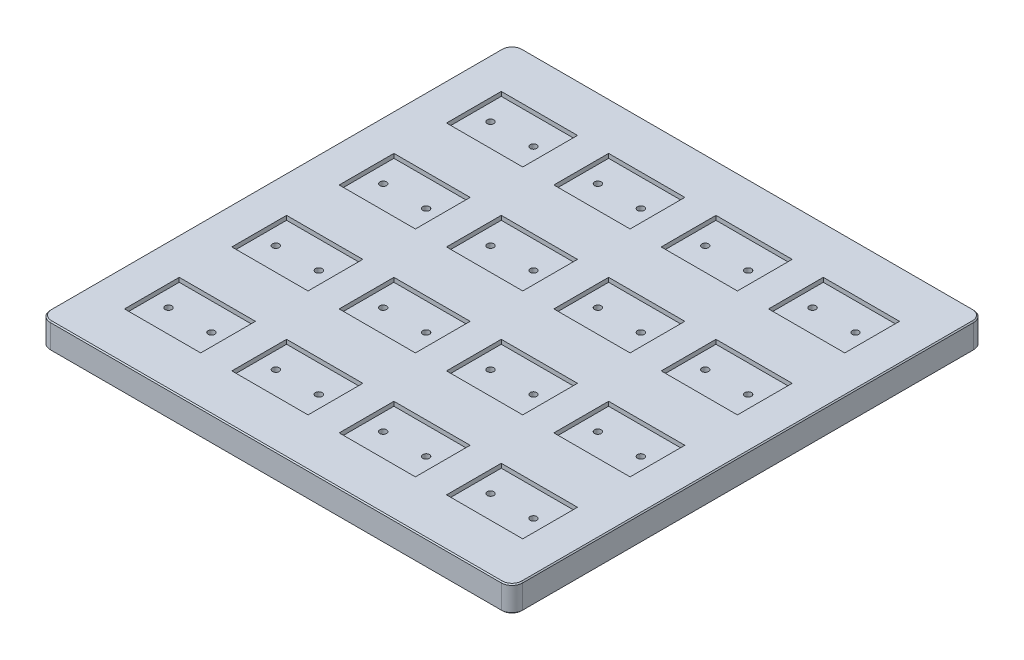
SolidWorks part; units mm, degrees
ref_plane "Front Plane" through (0, 0, 0) normal (0, 0, 1) x (1, 0, 0)
ref_plane "Top Plane" through (0, 0, 0) normal (0, 1, 0) x (1, 0, 0)
ref_plane "Right Plane" through (0, 0, 0) normal (1, 0, 0) x (0, 0, -1)
sketch "Sketch1" plane through (0, 0, 0) normal (0, 1, 0) x (1, 0, 0)
  line L1 (0, 0) -> (220, 0)
  line L2 (0, 0) -> (0, 220)
  line L3 (0, 220) -> (220, 220)
  line L4 (220, 0) -> (220, 220)
  dimension "D1" = 220
  dimension "D2" = 220
extrude "Boss-Extrude1" add sketch "Sketch1" along normal blind 12
sketch "Sketch2" plane through (0, 12, 0) normal (0, 1, 0) x (1, 0, 0)
  line L2 (0, 220) -> (0, 0) construction
  line L3 (17.25, 47.75) -> (52.75, 47.75)
  line L4 (17.25, 47.75) -> (17.25, 22.25)
  line L5 (17.25, 22.25) -> (52.75, 22.25)
  line L6 (52.75, 47.75) -> (52.75, 22.25)
  line L7 (0, 0) -> (220, 0) construction
  dimension "D1" = 25.5
  dimension "D2" = 35.5
  dimension "D3" = 17.25
  dimension "D4" = 22.25
extrude "Cut-Extrude1" cut sketch "Sketch2" against normal blind 2
pattern_linear "LPattern1" count 4 spacing 50 along (0, 0, -1) count 4 spacing 50 along (1, 0, 0) of "Cut-Extrude1"
sketch "Sketch3" plane through (0, 10, 0) normal (0, 1, 0) x (1, 0, 0)
  line L0 (35, 35) -> (35, 47.75) construction
  line L1 (35, 35) -> (52.75, 35) construction
  line L2 (52.75, 47.75) -> (17.25, 47.75) construction
  line L3 (52.75, 22.25) -> (52.75, 47.75) construction
  circle A0 centre (25, 35) radius 1.55
  circle A1 centre (45, 35) radius 1.55
  dimension "D1" = 3.1
  dimension "D2" = 20
extrude "Cut-Extrude2" cut sketch "Sketch3" against normal through all
pattern_linear "LPattern2" count 4 spacing 50 along (0, 0, -1) count 4 spacing 50 along (1, 0, 0) of "Cut-Extrude2"
sketch "Sketch4" plane through (0, 0, 0) normal (0, -1, 0) x (1, 0, 0)
  line L0 (0, -220) -> (0, 0) construction
  line L1 (10, -10) -> (210, -10)
  line L2 (10, -10) -> (10, -210)
  line L3 (10, -210) -> (210, -210)
  line L4 (210, -10) -> (210, -210)
  line L5 (220, -220) -> (0, -220) construction
  dimension "D1" = 200
  dimension "D2" = 200
  dimension "D3" = 10
  dimension "D4" = 10
extrude "Cut-Extrude3" cut sketch "Sketch4" against normal blind 3
fillet "Fillet1" radius 5 4 edges at (0, 6, -220) (0, 6, 0) (220, 6, 0) (220, 6, -220)
chamfer "Chamfer1" distance 0.5 angle 45 16 edges at (0, 0, -110) (1.4645, 0, -1.4645) (1.4645, 0, -218.5355) (110, 0, 0) (110, 0, -220) (218.5355, 0, -1.4645) (218.5355, 0, -218.5355) (220, 0, -110) (0, 12, -110) (1.4645, 12, -1.4645) (1.4645, 12, -218.5355) (110, 12, 0) (110, 12, -220) (218.5355, 12, -1.4645) (218.5355, 12, -218.5355) (220, 12, -110)
